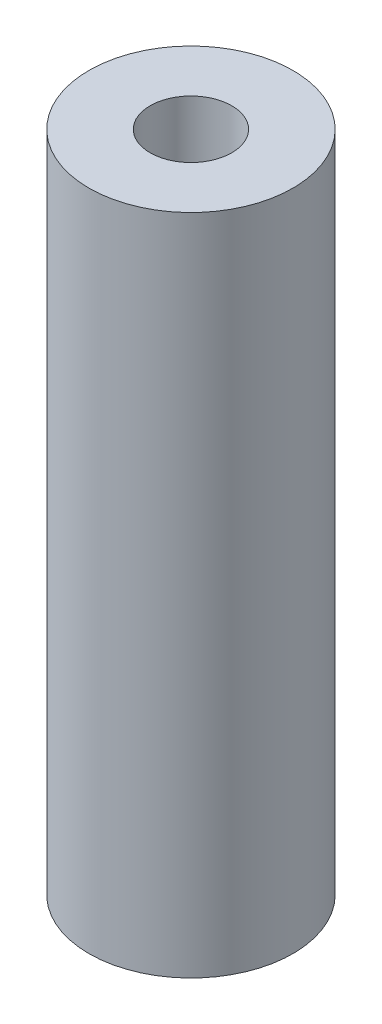
SolidWorks part; units mm, degrees
material "PVC Rígido"
ref_plane "Alzado" through (0, 0, 0) normal (0, 0, 1) x (1, 0, 0)
ref_plane "Planta" through (0, 0, 0) normal (0, 1, 0) x (1, 0, 0)
ref_plane "Vista lateral" through (0, 0, 0) normal (1, 0, 0) x (0, 0, -1)
sketch "Croquis2" plane through (0, 0, 0) normal (0, 1, 0) x (1, 0, 0)
  circle A0 centre (0, 0) radius 10
  circle A1 centre (0, 0) radius 4
  dimension "D1" = 20
  dimension "D2" = 8
extrude "Saliente-Extruir1" add sketch "Croquis2" along normal blind 65
